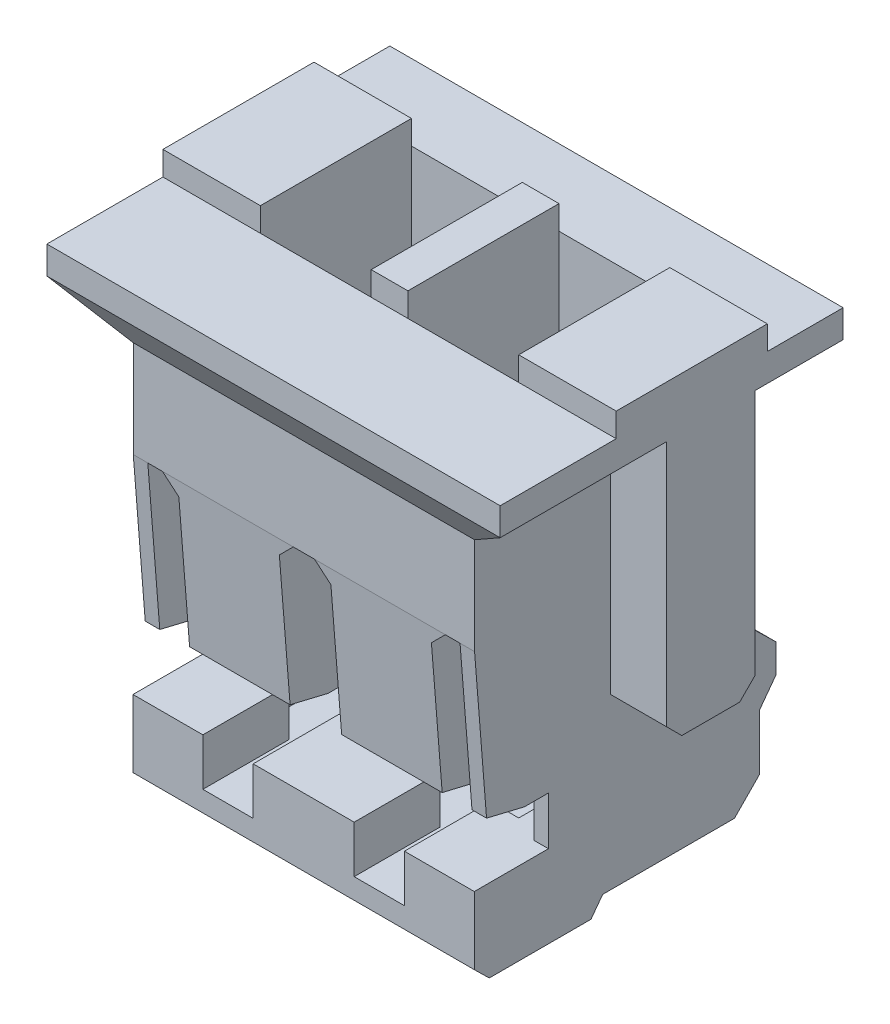
SolidWorks part; units mm, degrees
ref_plane "Front" through (0, 0, 0) normal (0, 0, 1) x (1, 0, 0)
ref_plane "Top" through (0, 0, 0) normal (0, 1, 0) x (1, 0, 0)
ref_plane "Right" through (0, 0, 0) normal (1, 0, 0) x (0, 0, -1)
sketch "草图1" plane through (0, 0, 0) normal (1, 0, 0) x (0, 0, -1)
  line L0 (0, 0) -> (0, 4.8) construction
  line L1 (0.0922, 0.0538) -> (3.1913, 0.0538) construction
  line L2 (0, 4.5622) -> (1.152, 4.5622)
  line L3 (1.152, 4.5622) -> (1.152, 4.8)
  line L4 (1.152, 4.8) -> (2.652, 4.8)
  line L5 (2.652, 4.8) -> (2.652, 4.5622)
  line L6 (2.652, 4.5622) -> (3.4049, 4.5622)
  line L7 (3.4049, 4.5622) -> (3.4049, 4.2872)
  line L8 (3.4049, 4.2872) -> (3.0717, 3.8383)
  line L9 (3.0717, 3.8383) -> (3.0717, 1.6848)
  line L10 (3.0717, 1.6848) -> (3.2952, 1.4657)
  line L11 (3.2952, 1.4657) -> (3.2952, 1.1845)
  line L12 (3.2952, 1.1845) -> (3.1324, 0.9651)
  line L13 (3.1324, 0.9651) -> (3.1324, 0.4111)
  line L14 (3.1324, 0.4111) -> (2.8824, 0.156)
  line L15 (2.8824, 0.156) -> (1.5734, 0.156)
  line L16 (1.5734, 0.156) -> (1.4577, 0)
  line L17 (1.4577, 0) -> (0.4481, 0)
  line L18 (0.4481, 0) -> (0.2992, 0.1459)
  line L19 (0.2992, 0.1459) -> (0.2992, 0.8179)
  line L20 (0.2992, 0.8179) -> (1.0353, 0.8179)
  line L21 (1.0353, 0.8179) -> (1.0353, 1.2973)
  line L22 (1.0353, 1.2973) -> (0.7973, 1.2973)
  line L23 (0.7973, 1.2973) -> (0.4207, 1.3877)
  line L24 (0.4207, 1.3877) -> (0.3019, 2.8792)
  line L25 (0.3019, 2.8792) -> (0.3019, 3.8406)
  line L26 (0.3019, 3.8406) -> (0, 4.2872)
  line L27 (0, 4.2872) -> (0, 4.5622)
  line L28 (0, 4.2872) -> (3.4049, 4.2872) construction
  line L29 (1.653, 1.8348) -> (1.803, 1.6848)
  line L30 (1.653, 4.2872) -> (2.5276, 4.2872)
  line L31 (1.653, 4.2872) -> (1.653, 1.8348)
  line L32 (1.803, 1.6848) -> (2.3776, 1.6848)
  line L33 (2.5276, 4.2872) -> (2.5276, 1.8348)
  line L34 (2.5276, 1.8348) -> (2.3776, 1.6848)
  point P32 (2.5276, 1.6848)
  point P33 (1.653, 1.6848)
  dimension "D1" = 4.8
  dimension "D2" = 4.8
  dimension "D3" = 1.5
extrude "凸台-拉伸1" add sketch "草图1" along normal blind 2.25
sketch "草图2" plane through (0, 0, 0) normal (0, 0, 1) x (1, 0, 0)
  line L0 (0, 0) -> (2.25, 0) construction
  line L1 (2.25, 4.2872) -> (1.6941, 3.8406)
  line L2 (2.25, 3.8406) -> (0, 3.8406) construction
  line L3 (1.6941, 3.8406) -> (1.6941, 2.8792)
  line L4 (2.25, 0) -> (0, 0) construction
  line L5 (2.25, 4.2872) -> (2.25, 0)
  line L6 (2.25, 0) -> (1.6941, 0)
  line L7 (2.25, 4.5622) -> (0, 4.5622) construction
  line L8 (0.1823, 4.5622) -> (1.2823, 4.5622)
  line L9 (0.1823, 4.5622) -> (0.1823, 5.0358)
  line L10 (0.1823, 5.0358) -> (1.2823, 5.0358)
  line L11 (1.2823, 4.5622) -> (1.2823, 5.0358)
  line L13 (2.25, 2.8792) -> (0, 2.8792) construction
  line L14 (1.2537, 2.7292) -> (1.2537, 0.8179)
  line L15 (2.25, 0.8179) -> (0, 0.8179) construction
  line L16 (1.2537, 0.8179) -> (1.4037, 0.8179)
  line L17 (0, 2.8792) -> (0.1059, 2.8792)
  line L18 (0.2559, 2.7292) -> (0.2559, 0.8179)
  line L19 (0.2559, 0.8179) -> (0, 0.8179)
  line L20 (0, 0.8179) -> (0, 2.8792)
  line L21 (1.6941, 0.8179) -> (1.6941, 0)
  line L22 (0.1059, 2.8792) -> (0.2559, 2.7292)
  line L23 (1.4037, 2.8792) -> (1.2537, 2.7292)
  line L25 (0.5014, 0.6566) -> (1.0004, 0.6566)
  line L26 (0.5014, 0.6566) -> (0.5014, 0.3493)
  line L27 (0.5014, 0.3493) -> (1.0004, 0.3493)
  line L28 (1.0004, 0.6566) -> (1.0004, 0.3493)
  line L29 (1.6941, 0.8179) -> (1.6941, 2.8792)
  line L31 (1.4037, 2.8792) -> (1.5498, 2.8792)
  line L33 (1.4037, 0.8179) -> (1.5498, 0.8179)
  line L34 (1.5498, 2.8792) -> (1.5498, 0.8179)
  point P18 (1.2537, 2.8792)
  point P26 (0.2559, 2.8792)
  dimension "D1" = 1.1
extrude "切除-拉伸1" cut sketch "草图2" against normal blind 1.5
sketch "草图5" plane through (0, 0, -1.5) normal (0, 0, 1) x (1, 0, 0)
  line L4 (0.1823, 4.8) -> (0.1823, 4.5622)
  line L5 (0.1823, 4.5622) -> (1.2823, 4.5622)
  line L6 (1.2823, 4.5622) -> (1.2823, 4.8)
  line L7 (1.2823, 4.8) -> (0.1823, 4.8)
  line L8 (0.1823, 4.8) -> (0.1823, 4.5622)
  line L9 (2.25, 0.057) -> (2.25, 4.2872)
  line L10 (2.25, 4.2872) -> (1.6941, 3.8406)
  line L11 (1.6941, 3.8406) -> (1.6941, 0.057)
  line L17 (1.6941, 0.057) -> (2.25, 0.057)
  line L18 (2.25, 0.057) -> (2.25, 4.2872)
  line L19 (2.25, 4.2872) -> (1.6941, 3.8406)
  line L20 (1.6941, 3.8406) -> (1.6941, 0.057)
  line L26 (1.6941, 0.057) -> (2.25, 0.057)
  line L27 (0.1823, 4.5622) -> (1.2823, 4.5622)
  line L28 (1.2823, 4.5622) -> (1.2823, 4.8)
  line L29 (1.2823, 4.8) -> (0.1823, 4.8)
  dimension "D1" = 0
  dimension "D2" = 0
extrude "切除-拉伸3" cut sketch "草图5" against normal through all
sketch "草图3" plane through (0, 0, 0) normal (-1, 0, 0) x (0, 0, 1)
  line L1 (-1.653, 1.8348) -> (-1.803, 1.6848) construction
  line L2 (-1.803, 1.6848) -> (-2.3776, 1.6848) construction
  line L3 (-2.3776, 1.6848) -> (-2.5276, 1.8348) construction
  line L5 (-2.5276, 4.2872) -> (-1.653, 4.2872) construction
  line L6 (-1.653, 4.2872) -> (-1.653, 1.8348)
  line L7 (-1.653, 1.8348) -> (-1.803, 1.6848)
  line L8 (-1.803, 1.6848) -> (-2.3776, 1.6848)
  line L9 (-2.3776, 1.6848) -> (-2.5276, 1.8348)
  line L10 (-2.5276, 1.8348) -> (-2.5276, 4.2872)
  line L11 (-2.5276, 4.2872) -> (-1.653, 4.2872)
extrude "凸台-拉伸2" add sketch "草图3" against normal up to surface (2.25 mm away) up to face at (2.25, 4.4998, -1.8598)
sketch "草图4" plane through (0, 4.5622, 0) normal (0, 1, 0) x (1, 0, 0)
  line L0 (0.1823, 1.902) -> (1.2823, 1.902) construction
  line L1 (0.1823, 2.652) -> (0.1823, 1.152) construction
  line L2 (1.2823, 2.652) -> (1.2823, 1.152) construction
  line L4 (1.2823, 2.652) -> (0.1823, 2.652)
  line L5 (1.2823, 2.652) -> (1.2823, 1.152)
  line L6 (1.2823, 1.152) -> (0.1823, 1.152)
  line L7 (0.1823, 2.652) -> (0.1823, 1.152)
  line L8 (1.2823, 2.652) -> (0.1823, 1.152) construction
  line L9 (1.2823, 1.152) -> (0.1823, 2.652) construction
  point P6 (0.7323, 1.902)
  point P11 (0.1497, 1.152)
extrude "切除-拉伸2" cut sketch "草图4" against normal up to surface (4.213 mm away) up to face at (0.7509, 0.3493, -0.8996)
sketch "草图6" plane through (0, 0, -1.0353) normal (0, 0, 1) x (1, 0, 0)
  line L4 (1.2537, 1.2973) -> (0.2559, 1.2973)
  line L5 (0.2559, 1.2973) -> (0.2559, 0.8179)
  line L6 (0.2559, 0.8179) -> (1.2537, 0.8179)
  line L7 (1.2537, 0.8179) -> (1.2537, 1.2973)
  line L8 (1.2537, 1.2973) -> (0.2559, 1.2973)
  line L9 (0.2559, 1.2973) -> (0.2559, 0.8179)
  line L10 (0.2559, 0.8179) -> (1.2537, 0.8179)
  line L11 (1.2537, 0.8179) -> (1.2537, 1.2973)
  dimension "D1" = 0
extrude "切除-拉伸4" cut sketch "草图6" against normal blind 0.2
sketch "草图7" plane through (0, 0, -0.2992) normal (0, 0, 1) x (1, 0, 0)
  line L0 (1.6941, 0.8179) -> (0, 0.8179) construction
  line L1 (0.5014, 0.3493) -> (1.0004, 0.3493)
  line L2 (0.5014, 0.3493) -> (0.5014, 0.8179)
  line L3 (0.5014, 0.8179) -> (1.0004, 0.8179)
  line L4 (1.0004, 0.3493) -> (1.0004, 0.8179)
  point P7 (1.0004, 0.3493)
  point P8 (0, 0)
  point P9 (1.0004, 0.3493)
extrude "切除-拉伸5" cut sketch "草图7" against normal through all
mirror "镜向1" of bodies 108 104
ref_plane "基准面1" through (0, 0, 0) normal (1, 0, 0) x (0, 0, -1)
